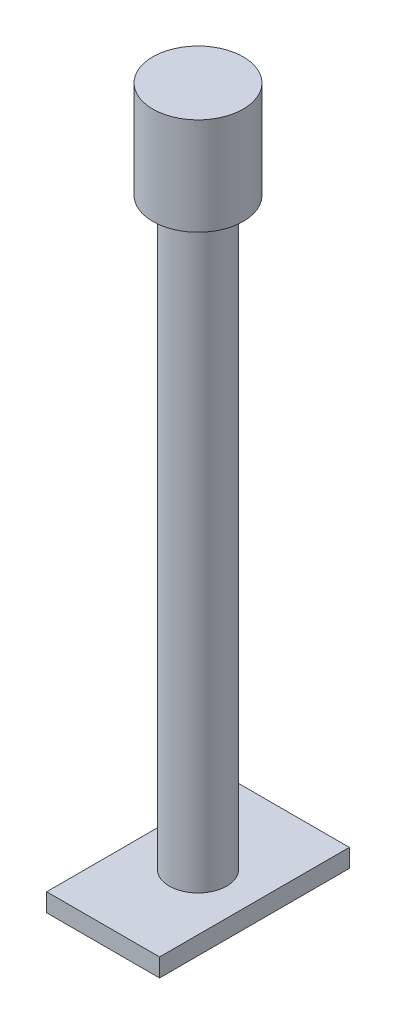
SolidWorks part; units mm, degrees
ref_plane "Front" through (0, 0, 0) normal (0, 0, 1) x (1, 0, 0)
ref_plane "Top" through (0, 0, 0) normal (0, 1, 0) x (1, 0, 0)
ref_plane "Right" through (0, 0, 0) normal (1, 0, 0) x (0, 0, -1)
sketch "Sketch1" plane through (0, 0, 0) normal (0, 1, 0) x (1, 0, 0)
  circle A0 centre (0, 0) radius 7.493
  dimension "D1" = 14.986
extrude "Boss-Extrude1" add sketch "Sketch1" along normal blind 152.4
sketch "Sketch2" plane through (0, 0, 0) normal (0, -1, 0) x (1, 0, 0)
  line L1 (-14.732, 24.765) -> (14.732, 24.765)
  line L2 (-14.732, 24.765) -> (-14.732, -24.765)
  line L3 (-14.732, -24.765) -> (14.732, -24.765)
  line L4 (14.732, 24.765) -> (14.732, -24.765)
  line L5 (-14.732, 24.765) -> (14.732, -24.765) construction
  line L6 (-14.732, -24.765) -> (14.732, 24.765) construction
  point P0 (0, 0)
  dimension "D1" = 29.464
  dimension "D2" = 49.53
extrude "Boss-Extrude2" add sketch "Sketch2" along normal blind 4.7625
sketch "Sketch3" plane through (0, 152.4, 0) normal (0, 1, 0) x (1, 0, 0)
  circle A0 centre (0, 0) radius 11.811
  dimension "D1" = 23.622
extrude "Boss-Extrude3" add sketch "Sketch3" along normal blind 25.4
